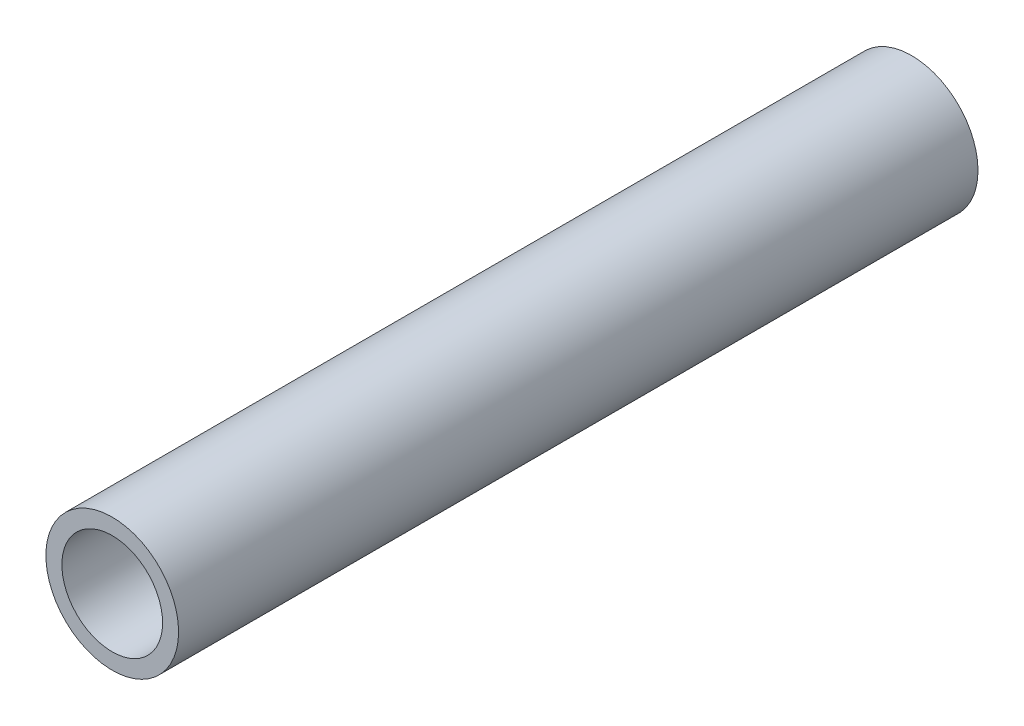
SolidWorks part; units mm, degrees
ref_plane "Alzado" through (0, 0, 0) normal (0, 0, 1) x (1, 0, 0)
ref_plane "Planta" through (0, 0, 0) normal (0, 1, 0) x (1, 0, 0)
ref_plane "Vista lateral" through (0, 0, 0) normal (1, 0, 0) x (0, 0, -1)
sketch "Croquis1" plane through (0, 0, 0) normal (0, 0, 1) x (1, 0, 0)
  circle A0 centre (0, 0) radius 41.5
  circle A1 centre (0, 0) radius 31.5
  dimension "D1" = 83
  dimension "D2" = 10
extrude "Saliente-Extruir1" add sketch "Croquis1" along normal blind 500
